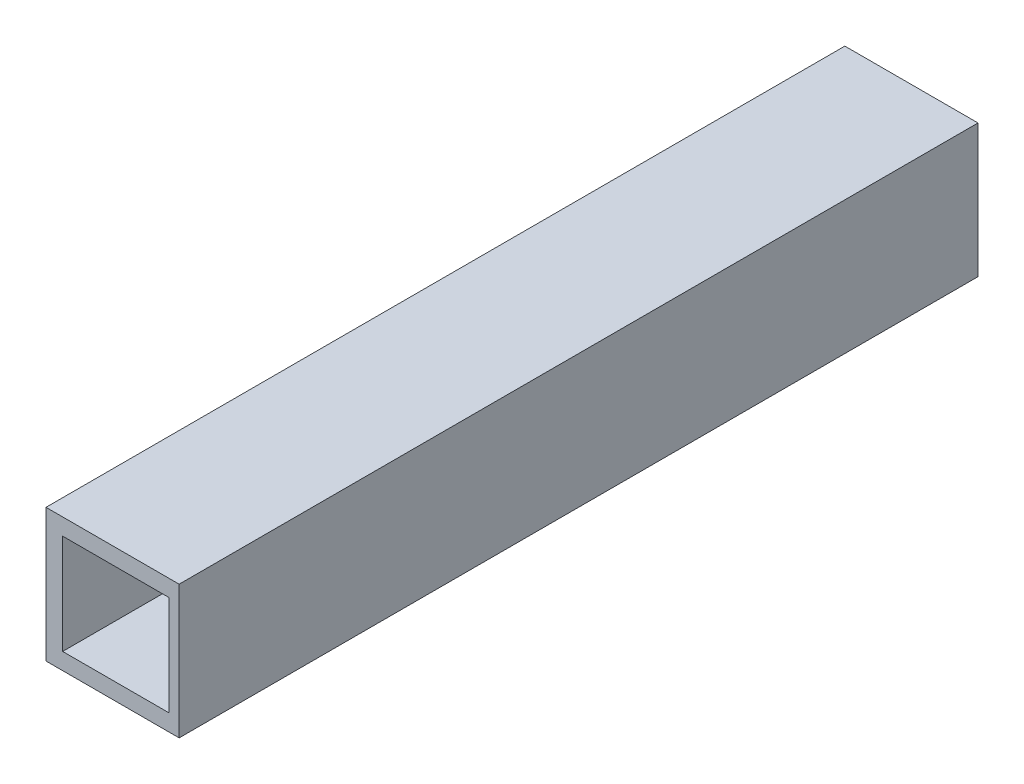
SolidWorks part; units mm, degrees
ref_plane "Front Plane" through (0, 0, 0) normal (0, 0, 1) x (1, 0, 0)
ref_plane "Top Plane" through (0, 0, 0) normal (0, 1, 0) x (1, 0, 0)
ref_plane "Right Plane" through (0, 0, 0) normal (1, 0, 0) x (0, 0, -1)
sketch "Sketch1" plane through (0, 0, 0) normal (0, 0, 1) x (1, 0, 0)
  line L1 (0, 0) -> (25.4, 0)
  line L2 (0, 0) -> (0, 25.4)
  line L3 (0, 25.4) -> (25.4, 25.4)
  line L4 (25.4, 0) -> (25.4, 25.4)
  dimension "D1" = 25.4
  dimension "D2" = 25.4
extrude "Boss-Extrude2" add sketch "Sketch1" along normal blind 152.4 contours L3 L4 L1 L2
sketch "Sketch2" plane through (0, 0, 0) normal (0, 0, -1) x (-1, 0, 0)
  line L0 (-23.4778, 22.225) -> (-3.175, 22.225)
  line L1 (-23.4778, 22.225) -> (-23.4778, 3.175)
  line L2 (-23.4778, 3.175) -> (-3.175, 3.175)
  line L3 (-3.175, 22.225) -> (-3.175, 3.175)
  line L4 (0, 0) -> (0, 25.4) construction
  line L5 (0, 0) -> (-25.4, 0) construction
  dimension "D1" = 3.175
  dimension "D2" = 3.175
extrude "Cut-Extrude1" cut sketch "Sketch2" against normal through all
